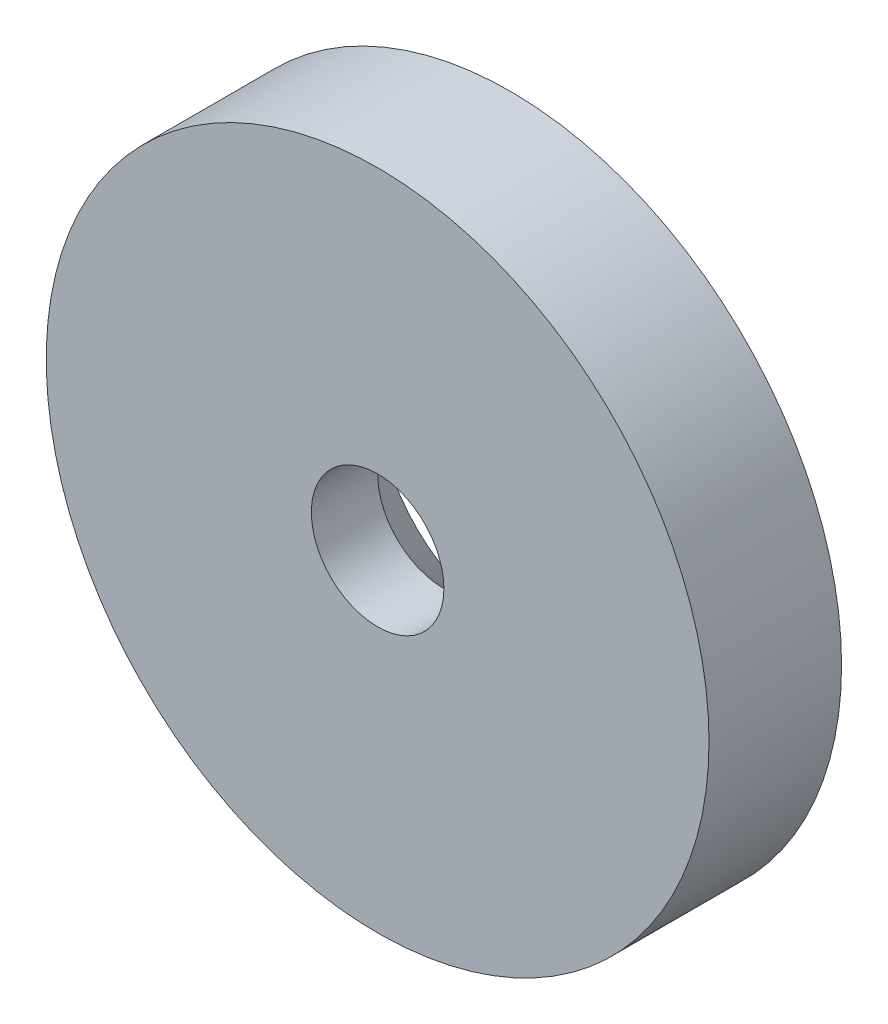
SolidWorks part; units mm, degrees
ref_plane "Front" through (0, 0, 0) normal (0, 0, 1) x (1, 0, 0)
ref_plane "Top" through (0, 0, 0) normal (0, 1, 0) x (1, 0, 0)
ref_plane "Right" through (0, 0, 0) normal (1, 0, 0) x (0, 0, -1)
sketch "草图1" plane through (0, 0, 0) normal (0, 0, 1) x (1, 0, 0)
  circle A0 centre (0, 0) radius 10
extrude "凸台-拉伸1" add sketch "草图1" along normal blind 4
sketch "草图2" plane through (0, 0, 4) normal (0, 0, 1) x (1, 0, 0)
  circle A0 centre (0, 0) radius 2
extrude "切除-拉伸1" cut sketch "草图2" against normal blind 4
chamfer "倒角1" distance 2 angle 45 1 edges at (2, 0, 0)
